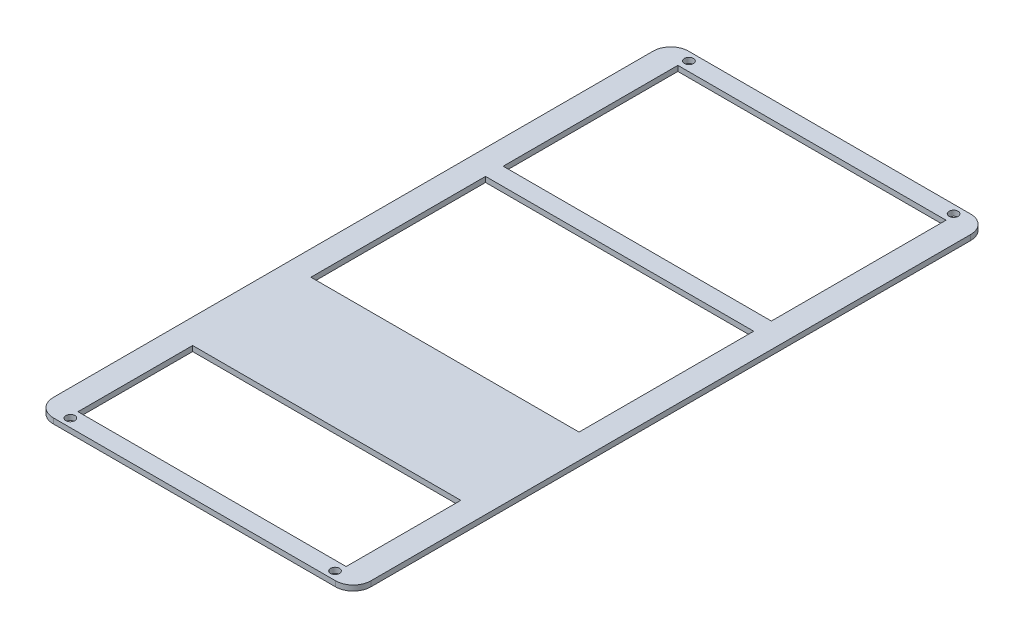
SolidWorks part; units mm, degrees
ref_plane "Front Plane" through (0, 0, 0) normal (0, 0, 1) x (1, 0, 0)
ref_plane "Top Plane" through (0, 0, 0) normal (0, 1, 0) x (1, 0, 0)
ref_plane "Right Plane" through (0, 0, 0) normal (1, 0, 0) x (0, 0, -1)
sketch "Sketch1" plane through (0, 0, 0) normal (0, 1, 0) x (1, 0, 0)
  line L0 (-75, 175.2871) -> (75, 175.2871) construction
  line L1 (-80, -180) -> (80, -180)
  line L2 (-90, -170) -> (-90, 170)
  line L3 (-80, 180) -> (80, 180)
  line L4 (90, -170) -> (90, 170)
  line L5 (-90, -180) -> (90, 180) construction
  line L6 (-90, 180) -> (90, -180) construction
  line L7 (-76, 71) -> (76, 71)
  line L8 (-76, 71) -> (-76, 170)
  line L9 (-76, 170) -> (76, 170)
  line L10 (76, 71) -> (76, 170)
  line L11 (-76, 71) -> (76, 170) construction
  line L12 (-76, 170) -> (76, 71) construction
  line L13 (-76, -170) -> (76, -170)
  line L14 (-76, -170) -> (-76, -105)
  line L15 (-76, -105) -> (76, -105)
  line L16 (76, -170) -> (76, -105)
  line L17 (-76, -170) -> (76, -105) construction
  line L18 (-76, -105) -> (76, -170) construction
  line L19 (-76, -38) -> (76, -38)
  line L20 (-76, -38) -> (-76, 61)
  line L21 (-76, 61) -> (76, 61)
  line L22 (76, -38) -> (76, 61)
  line L23 (-76, -38) -> (76, 61) construction
  line L24 (-76, 61) -> (76, -38) construction
  line L25 (0, 0) -> (63.5784, 0) construction
  circle A0 centre (-75, 175.2871) radius 2.55
  circle A1 centre (75, 175.2871) radius 2.55
  circle A2 centre (-75, -175.2871) radius 2.55
  circle A3 centre (75, -175.2871) radius 2.55
  arc A4 (-90, -170) -> (-80, -180) centre (-80, -170) ccw
  arc A5 (80, -180) -> (90, -170) centre (80, -170) ccw
  arc A6 (90, 170) -> (80, 180) centre (80, 170) ccw
  arc A7 (-80, 180) -> (-90, 170) centre (-80, 170) ccw
  point P0 (0, 0)
  point P6 (0, 120.5)
  point P11 (0, -137.5)
  point P16 (0, 11.5)
  point P21 (0, 71)
  point P22 (0, 170)
  point P23 (0, 61)
  point P24 (0, -105)
  point P29 (0, 175.2871)
  dimension "D12" = 5.1
  dimension "D14" = 10
  dimension "D1" = 180
  dimension "D2" = 360
  dimension "D3" = 152
  dimension "D4" = 99
  dimension "D5" = 99
  dimension "D6" = 10
  dimension "D7" = 10
  dimension "D8" = 152
  dimension "D9" = 152
  dimension "D10" = 65
  dimension "D11" = 10
  dimension "D13" = 150
extrude "Boss-Extrude1" add sketch "Sketch1" along normal blind 3
